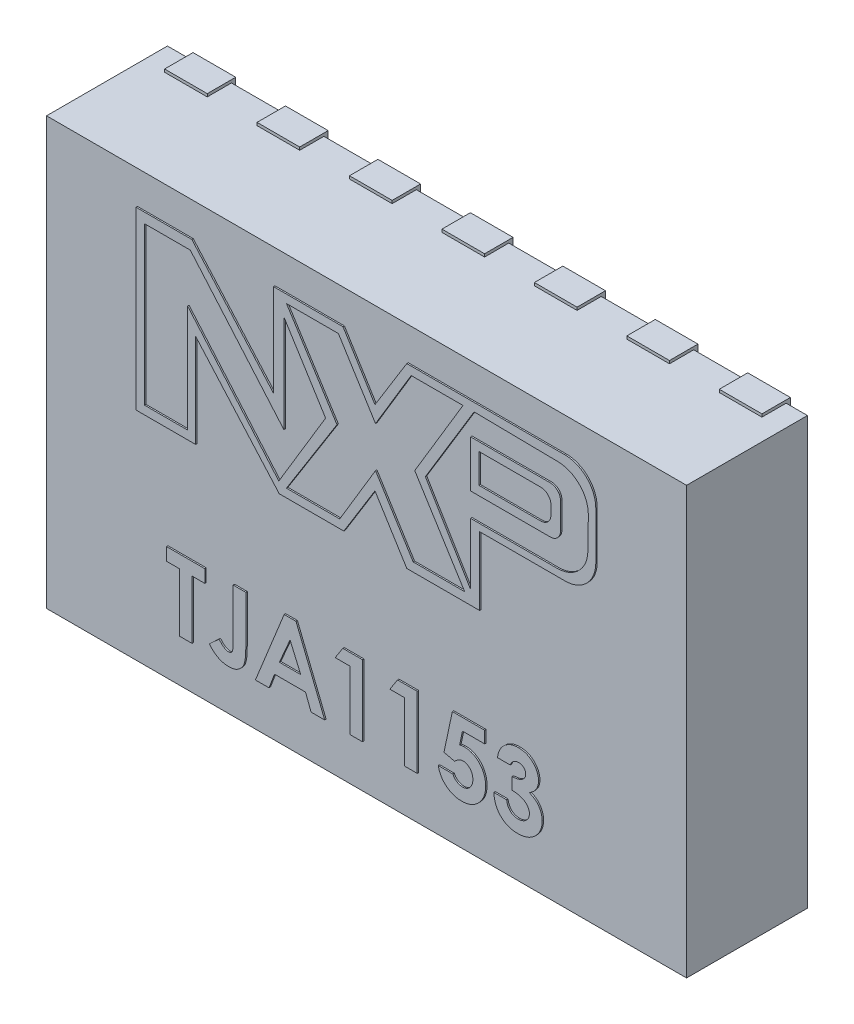
SolidWorks part; units mm, degrees
ref_plane "Front Plane" through (0, 0, 0) normal (0, 0, 1) x (1, 0, 0)
ref_plane "Top Plane" through (0, 0, 0) normal (0, 1, 0) x (1, 0, 0)
ref_plane "Right Plane" through (0, 0, 0) normal (1, 0, 0) x (0, 0, -1)
sketch "Sketch1" plane through (0, 0, 0) normal (0, 0, 1) x (1, 0, 0)
  line L1 (2.25, 1.5) -> (-2.25, 1.5)
  line L2 (2.25, 1.5) -> (2.25, -1.5)
  line L3 (2.25, -1.5) -> (-2.25, -1.5)
  line L4 (-2.25, 1.5) -> (-2.25, -1.5)
  line L5 (2.25, 1.5) -> (-2.25, -1.5) construction
  line L6 (2.25, -1.5) -> (-2.25, 1.5) construction
  point P0 (0, 0)
  dimension "D1" = 4.5
  dimension "D2" = 3
extrude "Boss-Extrude1" add sketch "Sketch1" along normal blind 0.85
sketch "Sketch2" plane through (0, 0, 0) normal (0, 0, -1) x (-1, 0, 0)
  line L0 (-2.25, 1.5) -> (2.25, 1.5) construction
  line L1 (2.1, 0.8) -> (-2.1, 0.8)
  line L2 (2.1, 0.8) -> (2.1, -0.8)
  line L3 (2.1, -0.8) -> (-2.1, -0.8)
  line L4 (-2.1, 0.8) -> (-2.1, -0.8)
  line L5 (2.1, 0.8) -> (-2.1, -0.8) construction
  line L6 (2.1, -0.8) -> (-2.1, 0.8) construction
  line L7 (-2.1, 1.6573) -> (-1.8, 1.6573)
  line L8 (-2.1, 1.6573) -> (-2.1, 1.1)
  line L9 (-2.1, 1.1) -> (-1.8, 1.1)
  line L10 (-1.8, 1.6573) -> (-1.8, 1.1)
  line L11 (-1.45, 1.6573) -> (-1.45, 1.1)
  line L12 (-1.45, 1.6573) -> (-1.15, 1.6573)
  line L13 (-1.15, 1.6573) -> (-1.15, 1.1)
  line L14 (-1.45, 1.1) -> (-1.15, 1.1)
  line L15 (-0.8, 1.6573) -> (-0.8, 1.1)
  line L16 (-0.8, 1.6573) -> (-0.5, 1.6573)
  line L17 (-0.5, 1.6573) -> (-0.5, 1.1)
  line L18 (-0.8, 1.1) -> (-0.5, 1.1)
  line L19 (-0.15, 1.6573) -> (-0.15, 1.1)
  line L20 (-0.15, 1.6573) -> (0.15, 1.6573)
  line L21 (0.15, 1.6573) -> (0.15, 1.1)
  line L22 (-0.15, 1.1) -> (0.15, 1.1)
  line L23 (0.5, 1.6573) -> (0.5, 1.1)
  line L24 (0.5, 1.6573) -> (0.8, 1.6573)
  line L25 (0.8, 1.6573) -> (0.8, 1.1)
  line L26 (0.5, 1.1) -> (0.8, 1.1)
  line L27 (1.15, 1.6573) -> (1.15, 1.1)
  line L28 (1.15, 1.6573) -> (1.45, 1.6573)
  line L29 (1.45, 1.6573) -> (1.45, 1.1)
  line L30 (1.15, 1.1) -> (1.45, 1.1)
  line L31 (1.8, 1.6573) -> (1.8, 1.1)
  line L32 (1.8, 1.6573) -> (2.1, 1.6573)
  line L33 (2.1, 1.6573) -> (2.1, 1.1)
  line L34 (1.8, 1.1) -> (2.1, 1.1)
  line L35 (0, 0) -> (1.2289, 0) construction
  line L36 (1.8, -1.1) -> (2.1, -1.1)
  line L37 (2.1, -1.6573) -> (2.1, -1.1)
  line L38 (1.8, -1.6573) -> (2.1, -1.6573)
  line L39 (1.8, -1.6573) -> (1.8, -1.1)
  line L40 (1.15, -1.1) -> (1.45, -1.1)
  line L41 (1.45, -1.6573) -> (1.45, -1.1)
  line L42 (1.15, -1.6573) -> (1.45, -1.6573)
  line L43 (1.15, -1.6573) -> (1.15, -1.1)
  line L44 (0.5, -1.1) -> (0.8, -1.1)
  line L45 (0.8, -1.6573) -> (0.8, -1.1)
  line L46 (0.5, -1.6573) -> (0.8, -1.6573)
  line L47 (0.5, -1.6573) -> (0.5, -1.1)
  line L48 (-0.15, -1.1) -> (0.15, -1.1)
  line L49 (0.15, -1.6573) -> (0.15, -1.1)
  line L50 (-0.15, -1.6573) -> (0.15, -1.6573)
  line L51 (-0.15, -1.6573) -> (-0.15, -1.1)
  line L52 (-0.8, -1.1) -> (-0.5, -1.1)
  line L53 (-0.5, -1.6573) -> (-0.5, -1.1)
  line L54 (-0.8, -1.6573) -> (-0.5, -1.6573)
  line L55 (-0.8, -1.6573) -> (-0.8, -1.1)
  line L56 (-1.45, -1.1) -> (-1.15, -1.1)
  line L57 (-1.15, -1.6573) -> (-1.15, -1.1)
  line L58 (-1.45, -1.6573) -> (-1.15, -1.6573)
  line L59 (-1.45, -1.6573) -> (-1.45, -1.1)
  line L60 (-1.8, -1.6573) -> (-1.8, -1.1)
  line L61 (-2.1, -1.1) -> (-1.8, -1.1)
  line L62 (-2.1, -1.6573) -> (-2.1, -1.1)
  line L63 (-2.1, -1.6573) -> (-1.8, -1.6573)
  point P0 (0, 0)
  dimension "D1" = 1.6
  dimension "D2" = 4.2
  dimension "D3" = 0.4
  dimension "D4" = 0.3
  dimension "D5" = 7
extrude "Boss-Extrude2" add sketch "Sketch2" along normal blind 0.03
sketch "Sketch3" plane through (0, 0, 0.85) normal (0, 0, 1) x (1, 0, 0)
  line L1 (-2.25, 1.5) -> (3.2924, 1.5)
  line L2 (-2.25, 1.5) -> (-2.25, 1.9025)
  line L3 (-2.25, 1.9025) -> (3.2924, 1.9025)
  line L4 (3.2924, 1.5) -> (3.2924, 1.9025)
  line L5 (-2.25, -1.5) -> (2.8586, -1.5)
  line L6 (-2.25, -1.5) -> (-2.25, -2.0374)
  line L7 (-2.25, -2.0374) -> (2.8586, -2.0374)
  line L8 (2.8586, -1.5) -> (2.8586, -2.0374)
extrude "Cut-Extrude1" cut sketch "Sketch3" against normal blind 2.03
sketch "Sketch4" plane through (0, -1.5, 0) normal (0, -1, 0) x (1, 0, 0)
  line L0 (-1.8, 0) -> (-1.8, -0.03) construction
  line L1 (-2.1, -0.03) -> (-1.8, -0.03)
  line L2 (-2.1, -0.03) -> (-2.1, 0.17)
  line L3 (-2.1, 0.17) -> (-1.8, 0.17)
  line L4 (-1.8, -0.03) -> (-1.8, 0.17)
  line L5 (-1.45, -0.03) -> (-1.45, 0.17)
  line L6 (-1.45, -0.03) -> (-1.15, -0.03)
  line L7 (-1.15, -0.03) -> (-1.15, 0.17)
  line L8 (-1.45, 0.17) -> (-1.15, 0.17)
  line L9 (-0.8, -0.03) -> (-0.8, 0.17)
  line L10 (-0.8, -0.03) -> (-0.5, -0.03)
  line L11 (-0.5, -0.03) -> (-0.5, 0.17)
  line L12 (-0.8, 0.17) -> (-0.5, 0.17)
  line L13 (-0.15, -0.03) -> (-0.15, 0.17)
  line L14 (-0.15, -0.03) -> (0.15, -0.03)
  line L15 (0.15, -0.03) -> (0.15, 0.17)
  line L16 (-0.15, 0.17) -> (0.15, 0.17)
  line L17 (0.5, -0.03) -> (0.5, 0.17)
  line L18 (0.5, -0.03) -> (0.8, -0.03)
  line L19 (0.8, -0.03) -> (0.8, 0.17)
  line L20 (0.5, 0.17) -> (0.8, 0.17)
  line L21 (1.15, -0.03) -> (1.15, 0.17)
  line L22 (1.15, -0.03) -> (1.45, -0.03)
  line L23 (1.45, -0.03) -> (1.45, 0.17)
  line L24 (1.15, 0.17) -> (1.45, 0.17)
  line L25 (1.8, -0.03) -> (1.8, 0.17)
  line L26 (1.8, -0.03) -> (2.1, -0.03)
  line L27 (2.1, -0.03) -> (2.1, 0.17)
  line L28 (1.8, 0.17) -> (2.1, 0.17)
  dimension "D1" = 0
  dimension "D2" = 0.2
  dimension "D3" = 7
extrude "Boss-Extrude3" add sketch "Sketch4" along normal blind 0.02
mirror "Mirror1" about plane through (0, 0, 0) normal (0, 1, 0) of "Boss-Extrude3"
sketch "Sketch8" plane through (0, 0, 0.85) normal (0, 0, 1) x (1, 0, 0)
  line L0 (70.666, 256.4211) -> (518.666, 256.4211) construction
  line L1 (-1.2186, 1.2679) -> (-0.6447, 0.6189)
  line L2 (-0.5532, 1.2103) -> (-0.188, 1.2103)
  line L3 (0.6998, 0.0824) -> (0.3376, 0.0824)
  line L4 (-0.6447, 1.2679) -> (-0.1555, 1.2679)
  line L5 (-1.1921, 0.6918) -> (-1.1921, 0.0329)
  line L6 (-0.188, 1.2103) -> (0.0731, 0.7923)
  line L7 (-0.1497, 0.0266) -> (-0.6039, 0.0266)
  line L8 (-1.1921, 0.0329) -> (-1.6111, 0.0329)
  line L9 (0.7662, 1.2103) -> (1.3564, 1.202)
  line L10 (0.742, 1.046) -> (0.742, 0.7163)
  line L11 (1.4057, 0.5003) -> (0.8054, 0.5003)
  line L12 (-1.552, 0.0924) -> (-1.552, 1.1975)
  line L13 (0.7998, 0.9863) -> (1.2343, 0.9863)
  line L14 (1.5693, 0.983) -> (1.5662, 0.7627)
  line L15 (1.3063, 0.9143) -> (1.3063, 0.852)
  line L16 (-1.6111, 0.0329) -> (-1.6111, 1.2679)
  line L17 (0.8054, 0.0202) -> (0.293, 0.0202)
  line L18 (-0.1981, 0.65) -> (-0.5532, 1.2103)
  line L19 (0.742, 0.5497) -> (0.742, 0.1156)
  line L20 (0.293, 1.2679) -> (1.4057, 1.2679)
  line L21 (-0.5714, 0.4334) -> (-0.5714, 1.1203)
  line L22 (0.3488, 0.6442) -> (0.6998, 0.0824)
  line L23 (0.293, 0.0202) -> (0.0692, 0.381)
  line L24 (-0.6069, 0.1027) -> (-1.248, 0.8474)
  line L25 (0.4233, 0.6442) -> (0.7662, 1.2103)
  line L26 (1.3016, 0.7163) -> (0.742, 0.7163)
  line L27 (1.6217, 1.0519) -> (1.6217, 0.7163)
  line L28 (-0.6039, 0.0266) -> (-1.1921, 0.6918)
  line L29 (0.0731, 0.5059) -> (-0.1786, 0.086)
  line L30 (0.0692, 0.9056) -> (0.293, 1.2679)
  line L31 (0.0731, 0.7923) -> (0.3236, 1.2103)
  line L32 (-0.5532, 0.086) -> (-0.1981, 0.65)
  line L33 (-0.5714, 1.1203) -> (-0.278, 0.65)
  line L34 (0.3236, 1.2103) -> (0.6882, 1.2103)
  line L35 (0.7998, 0.9863) -> (0.7998, 0.78)
  line L36 (-0.1786, 0.086) -> (-0.5532, 0.086)
  line L37 (0.7998, 0.78) -> (1.2343, 0.78)
  line L38 (0.3376, 0.0824) -> (0.0731, 0.5059)
  line L39 (0.742, 1.046) -> (1.3016, 1.046)
  line L40 (0.8054, 0.5003) -> (0.8054, 0.0202)
  line L41 (-1.2291, 1.1975) -> (-0.5714, 0.4334)
  line L42 (1.3736, 0.974) -> (1.3736, 0.7883)
  line L43 (-0.1555, 1.2679) -> (0.0692, 0.9056)
  line L44 (0.0692, 0.381) -> (-0.1497, 0.0266)
  line L45 (-1.248, 0.0924) -> (-1.552, 0.0924)
  line L46 (1.3503, 0.5497) -> (0.742, 0.5497)
  line L47 (-1.6111, 1.2679) -> (-1.2186, 1.2679)
  line L48 (-0.278, 0.65) -> (-0.6069, 0.1027)
  line L49 (0.6882, 1.2103) -> (0.3488, 0.6442)
  line L50 (-0.6447, 0.6189) -> (-0.6447, 1.2679)
  line L51 (-1.552, 1.1975) -> (-1.2291, 1.1975)
  line L52 (-1.248, 0.8474) -> (-1.248, 0.0924)
  line L53 (0.742, 0.1156) -> (0.4233, 0.6442)
  line L54 (-1.6111, -1.125) -> (1.3503, -1.125) construction
  arc A0 (1.3016, 1.046) -> (1.3736, 0.974) centre (1.3016, 0.974) cw
  arc A1 (1.4057, 1.2679) -> (1.6217, 1.0519) centre (1.4057, 1.0519) cw
  arc A2 (1.3736, 0.7883) -> (1.3016, 0.7163) centre (1.3016, 0.7883) cw
  arc A3 (1.6217, 0.7163) -> (1.4057, 0.5003) centre (1.4057, 0.7163) cw
  arc A4 (1.2343, 0.9863) -> (1.3063, 0.9143) centre (1.2343, 0.9143) cw
  arc A5 (1.5662, 0.7627) -> (1.3503, 0.5497) centre (1.3503, 0.7657) cw
  arc A6 (1.2343, 0.78) -> (1.3063, 0.852) centre (1.2343, 0.852) ccw
  arc A7 (1.3564, 1.202) -> (1.5693, 0.983) centre (1.3533, 0.9861) cw
  text T0 "<b>TJA1145A</b>" font "Century Gothic" height 0.5
extrude "Boss-Extrude4" add sketch "Sketch8" along normal blind 0.01 contours A3 L27 A1 L20 L30 L43 L4 L50 L1 L47 L16 L8 L5 L28 L7 L44 L23 L17 L40 L11 L34 L49 L22 L3 L38 L29 L36 L32 L18 L2 L6 L31 L24 L52 L45 L12 L51 L41 L21 L33 L48 L9 A7 L14 A5 L46 L19 L53 | A2 L42 A0 L39 L10 L26 A6 L37 L35 L13 A4 L15
sketch "Sketch9" plane through (0, 0, 0.85) normal (0, 0, 1) x (1, 0, 0)
  line L0 (-1.4028, -1.1911) -> (1.6601, -1.1911) construction
  text T0 "<b>TJA1153</b>" font "Century Gothic" height 0.5
extrude "Boss-Extrude5" add sketch "Sketch9" along normal blind 0.01
